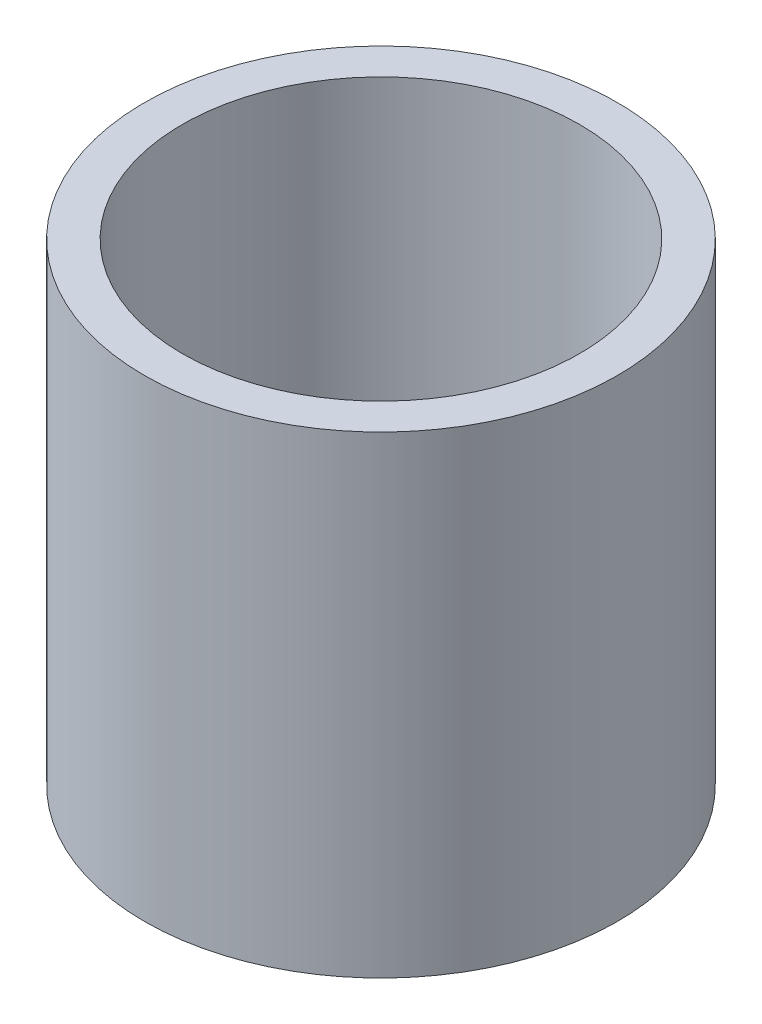
SolidWorks part; units mm, degrees
ref_plane "Front Plane" through (0, 0, 0) normal (0, 0, 1) x (1, 0, 0)
ref_plane "Top Plane" through (0, 0, 0) normal (0, 1, 0) x (1, 0, 0)
ref_plane "Right Plane" through (0, 0, 0) normal (1, 0, 0) x (0, 0, -1)
sketch "Sketch1" plane through (0, 0, 0) normal (0, 1, 0) x (1, 0, 0)
  circle A0 centre (0.8667, -1.1917) radius 12.5
  dimension "D1" = 25
extrude "Boss-Extrude1" add sketch "Sketch1" along normal blind 25
shell "Shell1" thickness 2
sketch "Sketch2" plane through (0, 2, 0) normal (0, 1, 0) x (1, 0, 0)
  circle A0 centre (0.8667, -1.1917) radius 3
extrude "Cut-Extrude1" cut sketch "Sketch2" against normal blind 25
